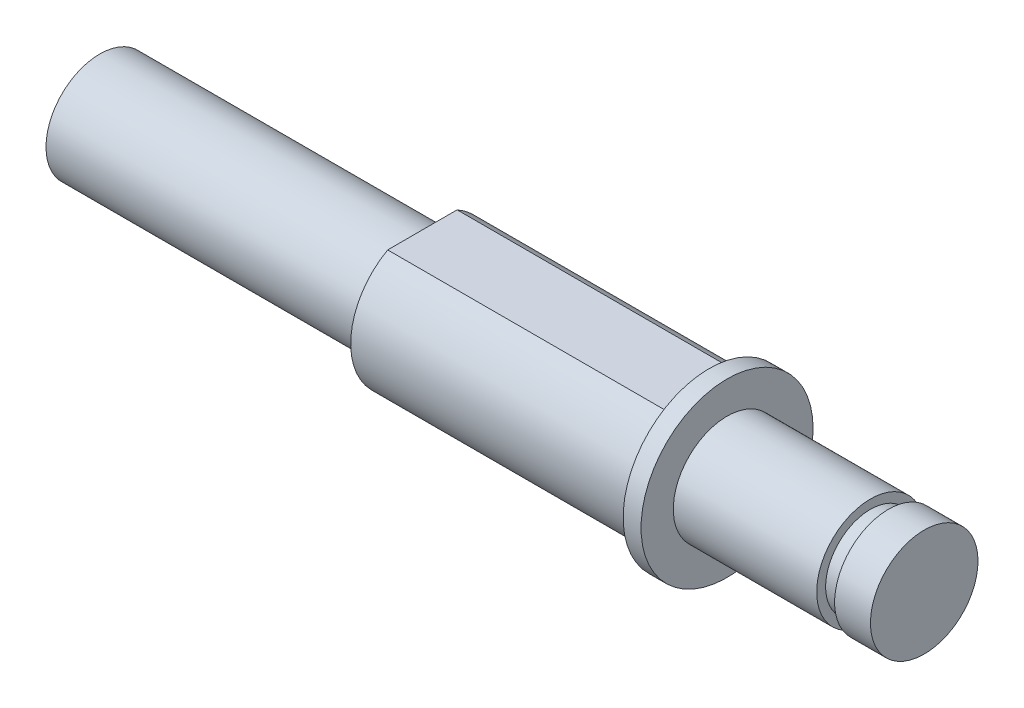
SolidWorks part; units mm, degrees
ref_plane "前视基准面" through (0, 0, 0) normal (0, 0, 1) x (1, 0, 0)
ref_plane "上视基准面" through (0, 0, 0) normal (0, 1, 0) x (1, 0, 0)
ref_plane "右视基准面" through (0, 0, 0) normal (1, 0, 0) x (0, 0, -1)
sketch "草图1" plane through (0, 0, 0) normal (1, 0, 0) x (0, 0, -1)
  circle A0 centre (0, 0) radius 1.5
extrude "凸台-拉伸1" add sketch "草图1" along normal blind 23
ref_plane "基准面1" through (9, 0, 0) normal (-1, 0, 0) x (0, 0, 1)
sketch "草图2" plane through (9, 0, 0) normal (-1, 0, 0) x (0, 0, 1)
  line L0 (0.9682, 1.75) -> (-0.9682, 1.75)
  arc A0 (-0.9682, 1.75) -> (0.9682, 1.75) centre (0, 0) ccw
  circle A1 centre (0, 0) radius 1.5
extrude "凸台-拉伸2" add sketch "草图2" against normal blind 8
sketch "草图3" plane through (17, 0, 0) normal (1, 0, 0) x (0, 0, -1)
  circle A0 centre (0, 0) radius 1.5
  circle A1 centre (0, 0) radius 2.4
extrude "凸台-拉伸3" add sketch "草图3" along normal blind 0.5
sketch "草图4" plane through (23, 0, 0) normal (1, 0, 0) x (0, 0, -1)
  circle A0 centre (0, 0) radius 1.25
  circle A1 centre (0, 0) radius 1.5
extrude "切除-拉伸1" cut sketch "草图4" against normal blind 0.5 from offset 1
